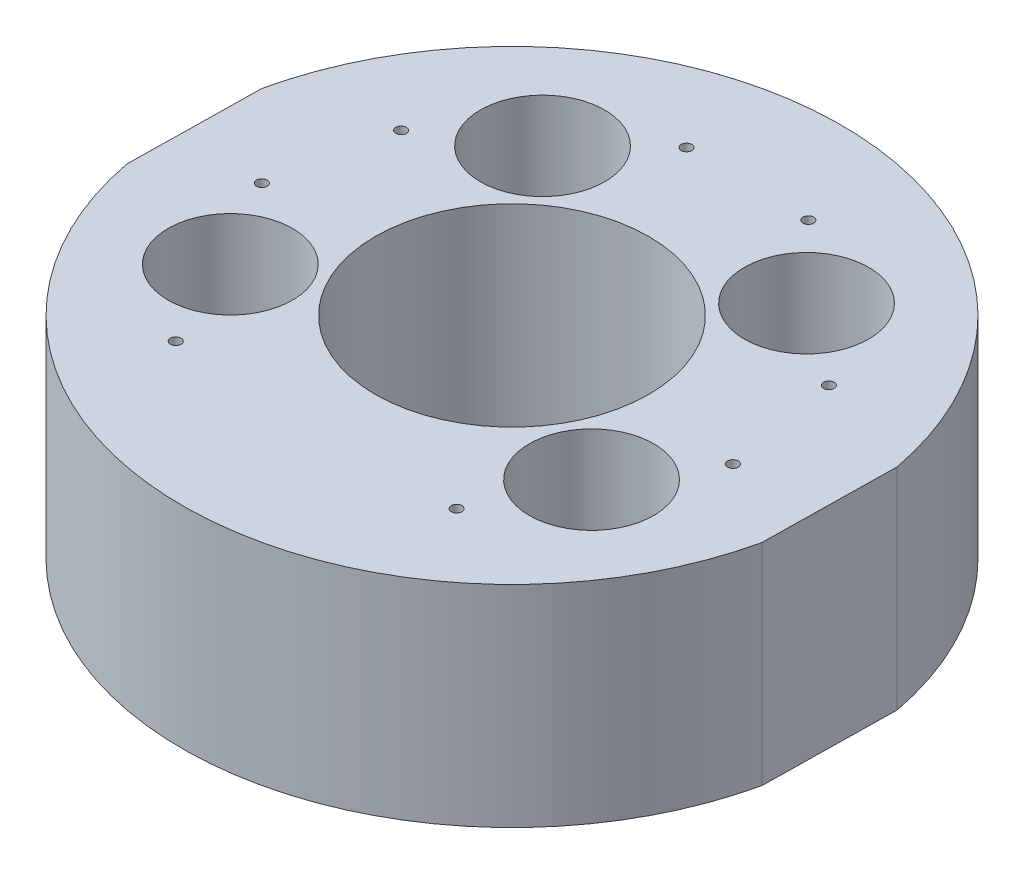
SolidWorks part; units mm, degrees
material "ABS"
ref_plane "Front Plane" through (0, 0, 0) normal (0, 0, 1) x (1, 0, 0)
ref_plane "Top Plane" through (0, 0, 0) normal (0, 1, 0) x (1, 0, 0)
ref_plane "Right Plane" through (0, 0, 0) normal (1, 0, 0) x (0, 0, -1)
sketch "Sketch1" plane through (0, 0, 0) normal (0, 1, 0) x (0.9999, 0, -0.0151)
  line L2 (-61.1695, 13.237) -> (-61.9456, -11.7509)
  line L3 (59.8522, 9.4781) -> (59.0761, -15.5098)
  circle A0 centre (-1.0467, -1.1364) radius 25.667
  arc A1 (59.8522, 9.4781) -> (-61.1695, 13.237) centre (-1.0467, -1.1364) ccw
  circle A2 centre (-25.2705, 29.6476) radius 11.666
  circle A3 centre (25.0408, 28.085) radius 11.666
  circle A4 centre (32.7953, -20.8636) radius 11.666
  circle A5 centre (-36.0477, -18.7254) radius 11.666
  arc A6 (-61.9456, -11.7509) -> (59.0761, -15.5098) centre (-1.0467, -1.1364) ccw
  dimension "D1" = 23.332
  dimension "D2" = 23.332
  dimension "D3" = 23.332
  dimension "D4" = 23.332
extrude "Boss-Extrude1" add sketch "Sketch1" along normal blind 39.5
extrude "Cut-Extrude1" cut sketch "Sketch2" against normal blind 8
sketch "Sketch2" plane through (-5.1081, 39.5, 5.9057) normal (0, 1, 0) x (0.9999, 0, 0.016)
  circle A0 centre (-13.0987, 51.8027) radius 1
  circle A1 centre (21.1033, 51.8027) radius 1
  circle A2 centre (40.6503, 18.1569) radius 1
  circle A3 centre (55.5443, -5.1203) radius 1
  circle A4 centre (20.5093, -31.747) radius 1
  circle A5 centre (-12.5047, -31.747) radius 1
  circle A6 centre (-47.5397, -5.1203) radius 1
  circle A7 centre (-32.6457, 18.1569) radius 1
extrude "Cut-Extrude2" cut sketch "Sketch3" against normal blind 12
sketch "Sketch3" plane through (-5.1081, 40.5, 5.9057) normal (0, 1, 0) x (0.9999, 0, 0.016)
  circle A0 centre (-7.6112, 48.2937) radius 1
  circle A1 centre (15.6158, 48.2937) radius 1
  circle A2 centre (44.7861, 23.8359) radius 1
  circle A3 centre (48.9213, 2.1196) radius 1
  circle A4 centre (30.7808, -31.347) radius 1
  circle A5 centre (-22.7762, -31.347) radius 1
  circle A6 centre (-40.9167, 2.1196) radius 1
  circle A7 centre (-36.7816, 23.8359) radius 1
